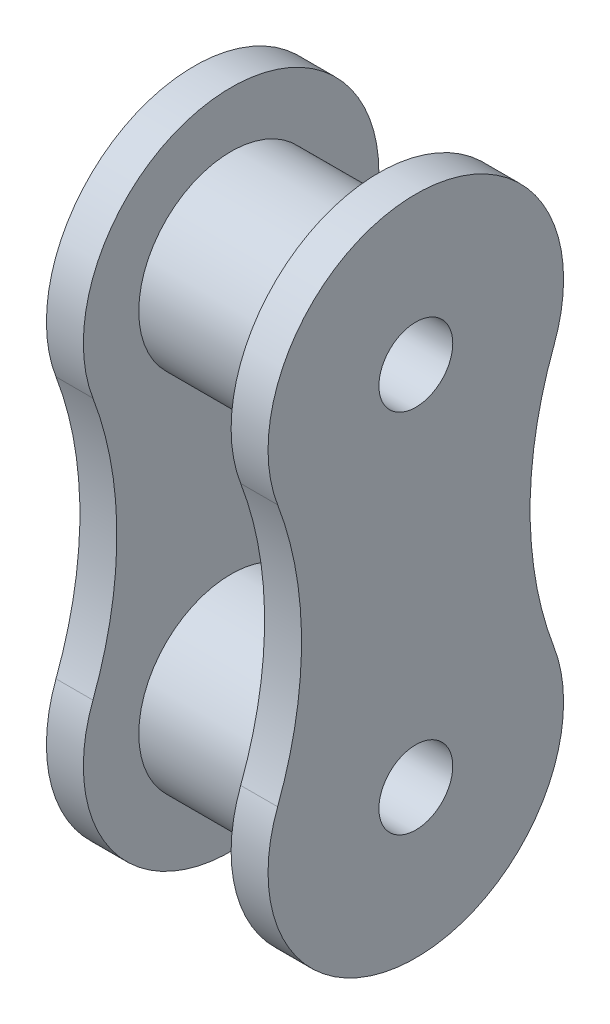
SolidWorks part; units mm, degrees
material "AISI 1045 Steel, cold drawn"
ref_plane "Front Plane" through (0, 0, 0) normal (1, 0, 0) x (0, 1, 0)
ref_plane "Top Plane" through (0, 0, 0) normal (0, 0, 1) x (0, 1, 0)
ref_plane "Right Plane" through (0, 0, 0) normal (0, 1, 0) x (-1, 0, 0)
sketch "Sketch1" plane through (0, 0, 0) normal (1, 0, 0) x (0, 1, 0)
  line L0 (0, 16.5238) -> (0, -13.2191) construction
  line L1 (-10.1503, 0) -> (13.0864, 0) construction
  circle A0 centre (-4.955, 0) radius 2.5
  circle A1 centre (4.955, 0) radius 2.5
  dimension "D1" = 5
  dimension "D2" = 9.91
extrude "Boss-Extrude1" add sketch "Sketch1" along normal mid plane 5
sketch "Sketch2" plane through (2.5, 0, 0) normal (1, 0, 0) x (0, 1, 0)
  line L0 (0, 5.072) -> (0, -6.8768) construction
  line L1 (-1.4158, 0) -> (2.2559, 0) construction
  circle A0 centre (-4.955, 0) radius 4
  circle A1 centre (4.955, 0) radius 4
  arc A2 (-3.5393, 3.7411) -> (3.5393, 3.7411) centre (0, 13.0938) ccw
  arc A3 (-3.5393, -3.7411) -> (3.5393, -3.7411) centre (0, -13.0938) cw
  circle A4 centre (-4.955, 0) radius 2.5 construction
  circle M3 centre (4.955, 0) radius 2.5
  dimension "D1" = 8
  dimension "D2" = 10
extrude "Boss-Extrude2" add sketch "Sketch2" along normal mid plane 1 contours A0 | A0 A3 A1 A2 | A1 M3 | M3
mirror "Mirror1" about plane through (0, 0, 0) normal (1, 0, 0) of "Boss-Extrude2"
sketch "Sketch3" plane through (3, 0, 0) normal (1, 0, 0) x (0, 1, 0)
  circle A0 centre (-4.955, 0) radius 1
  circle A1 centre (4.955, 0) radius 1
  arc A2 (-3.5393, 3.7411) -> (-3.5393, -3.7411) centre (-4.955, 0) ccw construction
  arc A3 (3.5393, -3.7411) -> (3.5393, 3.7411) centre (4.955, 0) ccw construction
  dimension "D1" = 2
extrude "Cut-Extrude1" cut sketch "Sketch3" against normal through all
